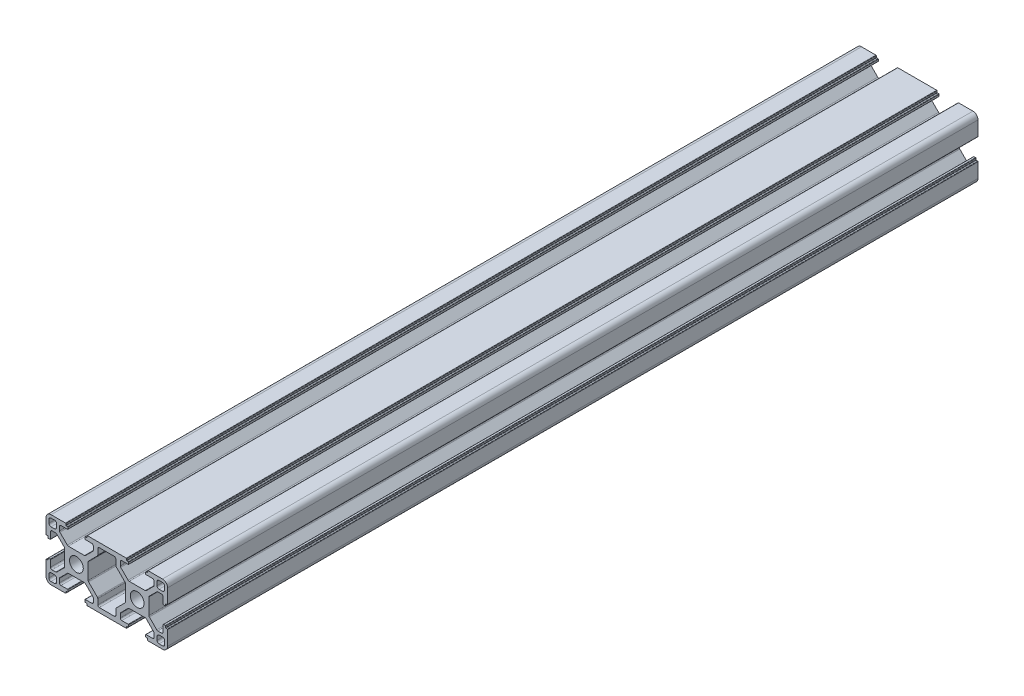
SolidWorks part; units mm, degrees
material "6063-T5"
ref_plane "Front Plane" through (0, 0, 0) normal (0, 0, 1) x (1, 0, 0)
ref_plane "Top Plane" through (0, 0, 0) normal (0, 1, 0) x (1, 0, 0)
ref_plane "Right Plane" through (0, 0, 0) normal (1, 0, 0) x (0, 0, -1)
sketch "Sketch1" plane through (0, 0, 0) normal (0, 0, 1) x (1, 0, 0)
  line L0 (2.5, 0) -> (9.6, 0)
  line L1 (60, 2.5) -> (60, 9.6)
  line L2 (57.5, 30) -> (50.4, 30)
  line L3 (0, 27.5) -> (0, 20.4)
  line L4 (21.0197, 10.536) -> (25.3303, 6.2253)
  line L5 (19.464, 21.0197) -> (23.1303, 24.686)
  line L6 (19.464, 8.9803) -> (23.1303, 5.314)
  line L7 (21.0197, 19.464) -> (25.3303, 23.7747)
  line L8 (11.0663, 9.2) -> (18.9337, 9.2)
  line L9 (9.2, 18.9337) -> (9.2, 11.0663)
  line L10 (41.0663, 9.2) -> (48.9337, 9.2)
  line L11 (40.536, 21.0197) -> (36.8697, 24.686)
  line L12 (50.8, 18.9337) -> (50.8, 11.0663)
  line L13 (38.9803, 10.536) -> (34.6697, 6.2253)
  line L14 (5.314, 23.1303) -> (8.9803, 19.464)
  line L15 (6.8697, 24.686) -> (10.536, 21.0197)
  line L16 (40.536, 8.9803) -> (36.8697, 5.314)
  line L17 (38.9803, 19.464) -> (34.6697, 23.7747)
  line L18 (5.314, 6.8697) -> (8.9803, 10.536)
  line L19 (6.8697, 5.314) -> (10.536, 8.9803)
  line L20 (36.65, 25.2163) -> (36.65, 27.05)
  line L21 (4.7837, 23.35) -> (2.95, 23.35)
  line L22 (4.7837, 6.65) -> (2.95, 6.65)
  line L23 (53.35, 25.2163) -> (53.35, 27.05)
  line L24 (53.1303, 24.686) -> (49.464, 21.0197)
  line L25 (54.686, 23.1303) -> (51.0197, 19.464)
  line L26 (54.686, 6.8697) -> (51.0197, 10.536)
  line L27 (53.1303, 5.314) -> (49.464, 8.9803)
  line L28 (11.0663, 20.8) -> (18.9337, 20.8)
  line L29 (41.0663, 20.8) -> (48.9337, 20.8)
  line L30 (20.8, 18.9337) -> (20.8, 11.0663)
  line L31 (39.2, 18.9337) -> (39.2, 11.0663)
  line L32 (6.65, 4.7837) -> (6.65, 2.95)
  line L33 (6.65, 27.05) -> (6.65, 25.2163)
  line L34 (23.35, 27.05) -> (23.35, 25.2163)
  line L35 (55.2163, 23.35) -> (57.05, 23.35)
  line L36 (55.2163, 6.65) -> (57.05, 6.65)
  line L37 (23.35, 4.7837) -> (23.35, 2.95)
  line L38 (36.65, 4.7837) -> (36.65, 2.95)
  line L39 (53.35, 4.7837) -> (53.35, 2.95)
  line L40 (34.45, 24.305) -> (34.45, 27.05)
  line L41 (25.55, 24.305) -> (25.55, 27.05)
  line L42 (25.55, 5.695) -> (25.55, 2.95)
  line L43 (34.45, 5.695) -> (34.45, 2.95)
  line L44 (26.3, 27.8) -> (33.7, 27.8)
  line L45 (7.4, 27.8) -> (10.6, 27.8)
  line L46 (7.4, 2.2) -> (10.5556, 2.2)
  line L47 (2.2, 22.6) -> (2.2, 19.4)
  line L48 (57.8, 22.6) -> (57.8, 19.4)
  line L49 (37.4, 27.8) -> (40.6, 27.8)
  line L50 (26.3, 2.2) -> (33.7, 2.2)
  line L51 (37.4, 2.2) -> (40.5556, 2.2)
  line L52 (9.6, 30) -> (2.5, 30)
  line L53 (19.2, 28) -> (19.2, 28.8)
  line L54 (10.7556, 2) -> (10.7556, 1.2)
  line L55 (10.8, 28) -> (10.8, 28.8)
  line L56 (19.4, 27.8) -> (22.6, 27.8)
  line L57 (40.8, 28) -> (40.8, 28.8)
  line L58 (19.1556, 2) -> (19.1556, 1.2)
  line L59 (20.3556, 0) -> (39.6, 0)
  line L60 (19.3556, 2.2) -> (22.6, 2.2)
  line L61 (49.1556, 2) -> (49.1556, 1.2)
  line L62 (40.7556, 2) -> (40.7556, 1.2)
  line L63 (49.2, 28) -> (49.2, 28.8)
  line L64 (49.4, 27.8) -> (52.6, 27.8)
  line L65 (39.6, 30) -> (20.4, 30)
  line L66 (50.3556, 0) -> (57.5, 0)
  line L67 (49.3556, 2.2) -> (52.6, 2.2)
  line L68 (4.2, 24.8) -> (2.45, 24.8)
  line L69 (2, 19.2) -> (1.2, 19.2)
  line L70 (58, 19.2) -> (58.8, 19.2)
  line L71 (2, 10.8) -> (1.2, 10.8)
  line L72 (0, 9.6) -> (0, 2.5)
  line L73 (2.2, 10.6) -> (2.2, 7.4)
  line L74 (5.2, 27.55) -> (5.2, 25.8)
  line L75 (58, 10.8) -> (58.8, 10.8)
  line L76 (60, 20.4) -> (60, 27.5)
  line L77 (57.8, 10.6) -> (57.8, 7.4)
  line L78 (55.8, 28.55) -> (57.55, 28.55)
  line L79 (58.55, 4.2) -> (58.55, 2.45)
  line L80 (4.2, 28.55) -> (2.45, 28.55)
  line L81 (1.45, 25.8) -> (1.45, 27.55)
  line L82 (55.8, 24.8) -> (57.55, 24.8)
  line L83 (1.45, 4.2) -> (1.45, 2.45)
  line L84 (2.45, 5.2) -> (4.2, 5.2)
  line L85 (5.2, 2.45) -> (5.2, 4.2)
  line L86 (54.8, 2.45) -> (54.8, 4.2)
  line L87 (55.8, 5.2) -> (57.55, 5.2)
  line L88 (4.2, 1.45) -> (2.45, 1.45)
  line L89 (58.55, 27.55) -> (58.55, 25.8)
  line L90 (19.4, 29) -> (20, 29)
  line L91 (54.8, 25.8) -> (54.8, 27.55)
  line L92 (57.55, 1.45) -> (55.8, 1.45)
  line L93 (9.8, 29.8) -> (9.8, 29.2)
  line L94 (10, 29) -> (10.6, 29)
  line L95 (20.2, 29.2) -> (20.2, 29.8)
  line L96 (9.8, 0.2) -> (9.8, 0.8)
  line L97 (0.2, 20.2) -> (0.8, 20.2)
  line L98 (1, 20) -> (1, 19.4)
  line L99 (1, 10.6) -> (1, 10)
  line L100 (0.8, 9.8) -> (0.2, 9.8)
  line L101 (10, 1) -> (10.5556, 1)
  line L102 (19.3556, 1) -> (19.9556, 1)
  line L103 (20.1556, 0.8) -> (20.1556, 0.2)
  line L104 (50.2, 29.2) -> (50.2, 29.8)
  line L105 (49.4, 29) -> (50, 29)
  line L106 (39.8, 29.8) -> (39.8, 29.2)
  line L107 (40, 29) -> (40.6, 29)
  line L108 (50.1556, 0.8) -> (50.1556, 0.2)
  line L109 (49.3556, 1) -> (49.9556, 1)
  line L110 (40, 1) -> (40.5556, 1)
  line L111 (39.8, 0.2) -> (39.8, 0.8)
  line L112 (59.8, 20.2) -> (59.2, 20.2)
  line L113 (59, 20) -> (59, 19.4)
  line L114 (59, 10.6) -> (59, 10)
  line L115 (59.2, 9.8) -> (59.8, 9.8)
  circle A0 centre (15, 15) radius 3.4
  circle A1 centre (45, 15) radius 3.4
  arc A2 (55.8, 1.45) -> (54.8, 2.45) centre (55.8, 2.45) cw
  arc A3 (57.55, 1.45) -> (58.55, 2.45) centre (57.55, 2.45) ccw
  arc A4 (57.55, 5.2) -> (58.55, 4.2) centre (57.55, 4.2) cw
  arc A5 (54.8, 4.2) -> (55.8, 5.2) centre (55.8, 4.2) cw
  arc A6 (55.8, 24.8) -> (54.8, 25.8) centre (55.8, 25.8) cw
  arc A7 (58.55, 25.8) -> (57.55, 24.8) centre (57.55, 25.8) cw
  arc A8 (57.55, 28.55) -> (58.55, 27.55) centre (57.55, 27.55) cw
  arc A9 (55.8, 28.55) -> (54.8, 27.55) centre (55.8, 27.55) ccw
  arc A10 (4.2, 5.2) -> (5.2, 4.2) centre (4.2, 4.2) cw
  arc A11 (4.2, 1.45) -> (5.2, 2.45) centre (4.2, 2.45) ccw
  arc A12 (2.45, 1.45) -> (1.45, 2.45) centre (2.45, 2.45) cw
  arc A13 (2.45, 5.2) -> (1.45, 4.2) centre (2.45, 4.2) ccw
  arc A14 (2.45, 24.8) -> (1.45, 25.8) centre (2.45, 25.8) cw
  arc A15 (4.2, 28.55) -> (5.2, 27.55) centre (4.2, 27.55) cw
  arc A16 (4.2, 24.8) -> (5.2, 25.8) centre (4.2, 25.8) ccw
  arc A17 (2.45, 28.55) -> (1.45, 27.55) centre (2.45, 27.55) ccw
  arc A18 (60, 27.5) -> (57.5, 30) centre (57.5, 27.5) ccw
  arc A19 (57.5, 0) -> (60, 2.5) centre (57.5, 2.5) ccw
  arc A20 (2.5, 0) -> (0, 2.5) centre (2.5, 2.5) cw
  arc A21 (2.5, 30) -> (0, 27.5) centre (2.5, 27.5) ccw
  arc A22 (53.35, 4.7837) -> (53.1303, 5.314) centre (52.6, 4.7837) ccw
  arc A23 (52.6, 2.2) -> (53.35, 2.95) centre (52.6, 2.95) ccw
  arc A24 (36.65, 2.95) -> (37.4, 2.2) centre (37.4, 2.95) ccw
  arc A25 (36.65, 4.7837) -> (36.8697, 5.314) centre (37.4, 4.7837) cw
  arc A26 (48.9337, 9.2) -> (49.464, 8.9803) centre (48.9337, 8.45) cw
  arc A27 (41.0663, 9.2) -> (40.536, 8.9803) centre (41.0663, 8.45) ccw
  arc A28 (57.8, 7.4) -> (57.05, 6.65) centre (57.05, 7.4) cw
  arc A29 (55.2163, 6.65) -> (54.686, 6.8697) centre (55.2163, 7.4) cw
  arc A30 (50.8, 11.0663) -> (51.0197, 10.536) centre (51.55, 11.0663) ccw
  arc A31 (50.8, 18.9337) -> (51.0197, 19.464) centre (51.55, 18.9337) cw
  arc A32 (55.2163, 23.35) -> (54.686, 23.1303) centre (55.2163, 22.6) ccw
  arc A33 (57.8, 22.6) -> (57.05, 23.35) centre (57.05, 22.6) ccw
  arc A34 (52.6, 27.8) -> (53.35, 27.05) centre (52.6, 27.05) cw
  arc A35 (53.35, 25.2163) -> (53.1303, 24.686) centre (52.6, 25.2163) cw
  arc A36 (48.9337, 20.8) -> (49.464, 21.0197) centre (48.9337, 21.55) ccw
  arc A37 (41.0663, 20.8) -> (40.536, 21.0197) centre (41.0663, 21.55) cw
  arc A38 (36.65, 25.2163) -> (36.8697, 24.686) centre (37.4, 25.2163) ccw
  arc A39 (36.65, 27.05) -> (37.4, 27.8) centre (37.4, 27.05) cw
  arc A40 (23.35, 2.95) -> (22.6, 2.2) centre (22.6, 2.95) cw
  arc A41 (23.35, 4.7837) -> (23.1303, 5.314) centre (22.6, 4.7837) ccw
  arc A42 (18.9337, 9.2) -> (19.464, 8.9803) centre (18.9337, 8.45) cw
  arc A43 (11.0663, 9.2) -> (10.536, 8.9803) centre (11.0663, 8.45) ccw
  arc A44 (6.65, 4.7837) -> (6.8697, 5.314) centre (7.4, 4.7837) cw
  arc A45 (7.4, 2.2) -> (6.65, 2.95) centre (7.4, 2.95) cw
  arc A46 (34.45, 27.05) -> (33.7, 27.8) centre (33.7, 27.05) ccw
  arc A47 (34.45, 24.305) -> (34.6697, 23.7747) centre (35.2, 24.305) ccw
  arc A48 (39.2, 18.9337) -> (38.9803, 19.464) centre (38.45, 18.9337) ccw
  arc A49 (39.2, 11.0663) -> (38.9803, 10.536) centre (38.45, 11.0663) cw
  arc A50 (34.45, 5.695) -> (34.6697, 6.2253) centre (35.2, 5.695) cw
  arc A51 (34.45, 2.95) -> (33.7, 2.2) centre (33.7, 2.95) cw
  arc A52 (25.55, 2.95) -> (26.3, 2.2) centre (26.3, 2.95) ccw
  arc A53 (25.55, 5.695) -> (25.3303, 6.2253) centre (24.8, 5.695) ccw
  arc A54 (20.8, 11.0663) -> (21.0197, 10.536) centre (21.55, 11.0663) ccw
  arc A55 (20.8, 18.9337) -> (21.0197, 19.464) centre (21.55, 18.9337) cw
  arc A56 (25.55, 24.305) -> (25.3303, 23.7747) centre (24.8, 24.305) cw
  arc A57 (25.55, 27.05) -> (26.3, 27.8) centre (26.3, 27.05) cw
  arc A58 (23.35, 27.05) -> (22.6, 27.8) centre (22.6, 27.05) ccw
  arc A59 (23.35, 25.2163) -> (23.1303, 24.686) centre (22.6, 25.2163) cw
  arc A60 (18.9337, 20.8) -> (19.464, 21.0197) centre (18.9337, 21.55) ccw
  arc A61 (11.0663, 20.8) -> (10.536, 21.0197) centre (11.0663, 21.55) cw
  arc A62 (6.65, 25.2163) -> (6.8697, 24.686) centre (7.4, 25.2163) ccw
  arc A63 (7.4, 27.8) -> (6.65, 27.05) centre (7.4, 27.05) ccw
  arc A64 (2.2, 7.4) -> (2.95, 6.65) centre (2.95, 7.4) ccw
  arc A65 (4.7837, 6.65) -> (5.314, 6.8697) centre (4.7837, 7.4) ccw
  arc A66 (9.2, 11.0663) -> (8.9803, 10.536) centre (8.45, 11.0663) cw
  arc A67 (9.2, 18.9337) -> (8.9803, 19.464) centre (8.45, 18.9337) ccw
  arc A68 (4.7837, 23.35) -> (5.314, 23.1303) centre (4.7837, 22.6) cw
  arc A69 (2.2, 22.6) -> (2.95, 23.35) centre (2.95, 22.6) cw
  arc A70 (49.2, 28) -> (49.4, 27.8) centre (49.4, 28) ccw
  arc A71 (49.4, 29) -> (49.2, 28.8) centre (49.4, 28.8) ccw
  arc A72 (50.2, 29.2) -> (50, 29) centre (50, 29.2) cw
  arc A73 (50.2, 29.8) -> (50.4, 30) centre (50.4, 29.8) cw
  arc A74 (59.8, 20.2) -> (60, 20.4) centre (59.8, 20.4) ccw
  arc A75 (59.2, 20.2) -> (59, 20) centre (59.2, 20) ccw
  arc A76 (59, 19.4) -> (58.8, 19.2) centre (58.8, 19.4) cw
  arc A77 (57.8, 19.4) -> (58, 19.2) centre (58, 19.4) ccw
  arc A78 (57.8, 10.6) -> (58, 10.8) centre (58, 10.6) cw
  arc A79 (59, 10.6) -> (58.8, 10.8) centre (58.8, 10.6) ccw
  arc A80 (59, 10) -> (59.2, 9.8) centre (59.2, 10) ccw
  arc A81 (59.8, 9.8) -> (60, 9.6) centre (59.8, 9.6) cw
  arc A82 (50.1556, 0.2) -> (50.3556, 0) centre (50.3556, 0.2) ccw
  arc A83 (50.1556, 0.8) -> (49.9556, 1) centre (49.9556, 0.8) ccw
  arc A84 (49.3556, 1) -> (49.1556, 1.2) centre (49.3556, 1.2) cw
  arc A85 (49.1556, 2) -> (49.3556, 2.2) centre (49.3556, 2) cw
  arc A86 (39.8, 0.2) -> (39.6, 0) centre (39.6, 0.2) cw
  arc A87 (40, 1) -> (39.8, 0.8) centre (40, 0.8) ccw
  arc A88 (40.5556, 1) -> (40.7556, 1.2) centre (40.5556, 1.2) ccw
  arc A89 (40.7556, 2) -> (40.5556, 2.2) centre (40.5556, 2) ccw
  arc A90 (20.1556, 0.2) -> (20.3556, 0) centre (20.3556, 0.2) ccw
  arc A91 (19.9556, 1) -> (20.1556, 0.8) centre (19.9556, 0.8) cw
  arc A92 (19.3556, 1) -> (19.1556, 1.2) centre (19.3556, 1.2) cw
  arc A93 (19.3556, 2.2) -> (19.1556, 2) centre (19.3556, 2) ccw
  arc A94 (9.8, 0.2) -> (9.6, 0) centre (9.6, 0.2) cw
  arc A95 (9.8, 0.8) -> (10, 1) centre (10, 0.8) cw
  arc A96 (10.5556, 1) -> (10.7556, 1.2) centre (10.5556, 1.2) ccw
  arc A97 (10.7556, 2) -> (10.5556, 2.2) centre (10.5556, 2) ccw
  arc A98 (0.2, 9.8) -> (0, 9.6) centre (0.2, 9.6) ccw
  arc A99 (1, 10) -> (0.8, 9.8) centre (0.8, 10) cw
  arc A100 (1.2, 10.8) -> (1, 10.6) centre (1.2, 10.6) ccw
  arc A101 (2.2, 10.6) -> (2, 10.8) centre (2, 10.6) ccw
  arc A102 (2.2, 19.4) -> (2, 19.2) centre (2, 19.4) cw
  arc A103 (1, 19.4) -> (1.2, 19.2) centre (1.2, 19.4) ccw
  arc A104 (0.8, 20.2) -> (1, 20) centre (0.8, 20) cw
  arc A105 (0, 20.4) -> (0.2, 20.2) centre (0.2, 20.4) ccw
  arc A106 (40.8, 28) -> (40.6, 27.8) centre (40.6, 28) cw
  arc A107 (40.6, 29) -> (40.8, 28.8) centre (40.6, 28.8) cw
  arc A108 (39.8, 29.2) -> (40, 29) centre (40, 29.2) ccw
  arc A109 (39.8, 29.8) -> (39.6, 30) centre (39.6, 29.8) ccw
  arc A110 (19.4, 27.8) -> (19.2, 28) centre (19.4, 28) cw
  arc A111 (19.4, 29) -> (19.2, 28.8) centre (19.4, 28.8) ccw
  arc A112 (20, 29) -> (20.2, 29.2) centre (20, 29.2) ccw
  arc A113 (20.2, 29.8) -> (20.4, 30) centre (20.4, 29.8) cw
  arc A114 (10.6, 27.8) -> (10.8, 28) centre (10.6, 28) ccw
  arc A115 (10.6, 29) -> (10.8, 28.8) centre (10.6, 28.8) cw
  arc A116 (9.8, 29.2) -> (10, 29) centre (10, 29.2) ccw
  arc A117 (9.6, 30) -> (9.8, 29.8) centre (9.6, 29.8) cw
  point P135 (0, 0)
extrude "Boss-Extrude1" add sketch "Sketch1" along normal blind 400 contours L52 A21 L3 A105 L97 A104 L98 A103 L69 A102 L47 A69 L21 A68 L14 A67 L9 A66 L18 A65 L22 A64 L73 A101 L71 A100 L99 A99 L100 A98 L72 A20 L0 A94 L96 A95 L101 A96 L54 A97 L46 A45 L32 A44 L19 A43 L8 A42 L6 A41 L37 A40 L60 A93 L58 A92 L102 A91 L103 A90 L59 A86 L111 A87 L110 A88 L62 A89 L51 A24 L38 A25 L16 A27 L10 A26 L27 A22 L39 A23 L67 A85 L61 A84 L109 A83 L108 A82 L66 A19 L1 A81 L115 A80 L114 A79 L75 A78 L77 A28 L36 A29 L26 A30 L12 A31 L25 A32 L35 A33 L48 A77 L70 A76 L113 A75 L112 A74 L76 A18 L2 A73 L104 A72 L105 A71 L63 A70 L64 A34 L23 A35 L24 A36 L29 A37 L11 A38 L20 A39 L49 A106 L57 A107 L107 A108 L106 A109 L65 A113 L95 A112 L90 A111 L53 A110 L56 A58 L34 A59 L5 A60 L28 A61 L15 A62 L33 A63 L45 A114 L55 A115 L94 A116 L93 A117 | A0 | A1 | L41 A57 L44 A46 L40 A47 L17 A48 L31 A49 L13 A50 L43 A51 L50 A52 L42 A53 L4 A54 L30 A55 L7 A56 | L85 A10 L84 A13 L83 A12 L88 A11 | L74 A16 L68 A14 L81 A17 L80 A15 | L89 A7 L82 A6 L91 A9 L78 A8 | L79 A3 L92 A2 L86 A5 L87 A4
